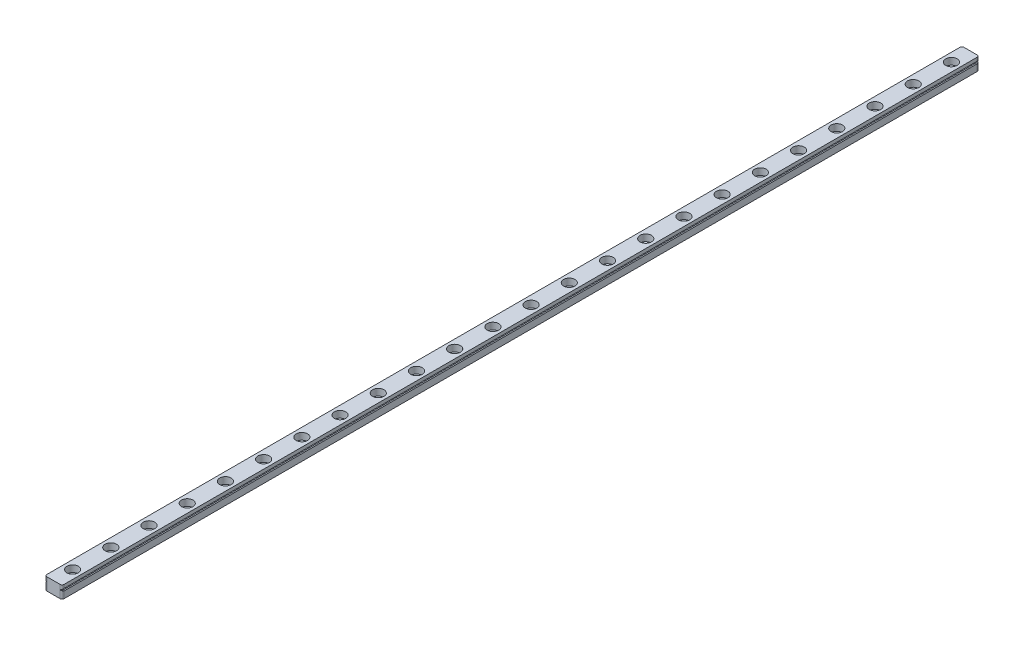
SolidWorks part; units mm, degrees
material "镀铬不锈钢"
ref_plane "前视基准面" through (0, 0, 0) normal (0, 0, 1) x (1, 0, 0)
ref_plane "上视基准面" through (0, 0, 0) normal (0, 1, 0) x (1, 0, 0)
ref_plane "右视基准面" through (0, 0, 0) normal (1, 0, 0) x (0, 0, -1)
sketch "草图1" plane through (0, 0, 0) normal (0, 0, 1) x (1, 0, 0)
  line L0 (-4.5, -3.6634) -> (4.5, -3.6634)
  line L1 (0, -3.6634) -> (0, 3.6634) construction
  line L2 (4.5, -3.6634) -> (4.5, -0.1634)
  line L3 (4.5, -0.1634) -> (4.1464, 0.1901)
  line L4 (4.1464, 0.1901) -> (3.6464, 0.1901)
  line L5 (3.6464, 0.1901) -> (3.6464, 0.6901)
  line L6 (3.6464, 0.6901) -> (4.1464, 0.6901)
  line L7 (4.1464, 0.6901) -> (4.5, 1.0437)
  line L8 (4.5, 1.0437) -> (4.5, 2.8366)
  line L9 (4.5, 2.8366) -> (-4.5, 2.8366)
  line L10 (-4.5, 1.0437) -> (-4.5, 2.8366)
  line L11 (-4.1464, 0.6901) -> (-4.5, 1.0437)
  line L12 (-3.6464, 0.6901) -> (-4.1464, 0.6901)
  line L13 (-3.6464, 0.1901) -> (-3.6464, 0.6901)
  line L14 (-4.1464, 0.1901) -> (-3.6464, 0.1901)
  line L15 (-4.5, -0.1634) -> (-4.1464, 0.1901)
  line L16 (-4.5, -3.6634) -> (-4.5, -0.1634)
  point P13 (0, 2.8366)
extrude "凸台-拉伸1" add sketch "草图1" along normal blind 480
sketch "草图2" plane through (0, 2.8366, 0) normal (0, 1, 0) x (1, 0, 0)
  line L0 (-4.5, -480) -> (-4.5, 0) construction
  line L1 (4.5, -480) -> (-4.5, -480) construction
  circle A0 centre (0, -470) radius 3
  dimension "D1" = 6
  dimension "D2" = 4.5
  dimension "D3" = 10
extrude "切除-拉伸1" cut sketch "草图2" against normal blind 3.5
sketch "草图3" plane through (0, -0.6634, 0) normal (0, 1, 0) x (1, 0, 0)
  circle A0 centre (0, -470) radius 1.75
  dimension "D1" = 3.5
extrude "切除-拉伸2" cut sketch "草图3" against normal through all
pattern_linear "阵列(线性)1" count 30 spacing 20 along (0, 0, -1) of "切除-拉伸1", "切除-拉伸2"
fillet "圆角1" radius 1 4 edges at (4.5, -1.9134, 0) (-4.5, -1.9134, 0) (4.5, -1.9134, 480) (-4.5, -1.9134, 480)
